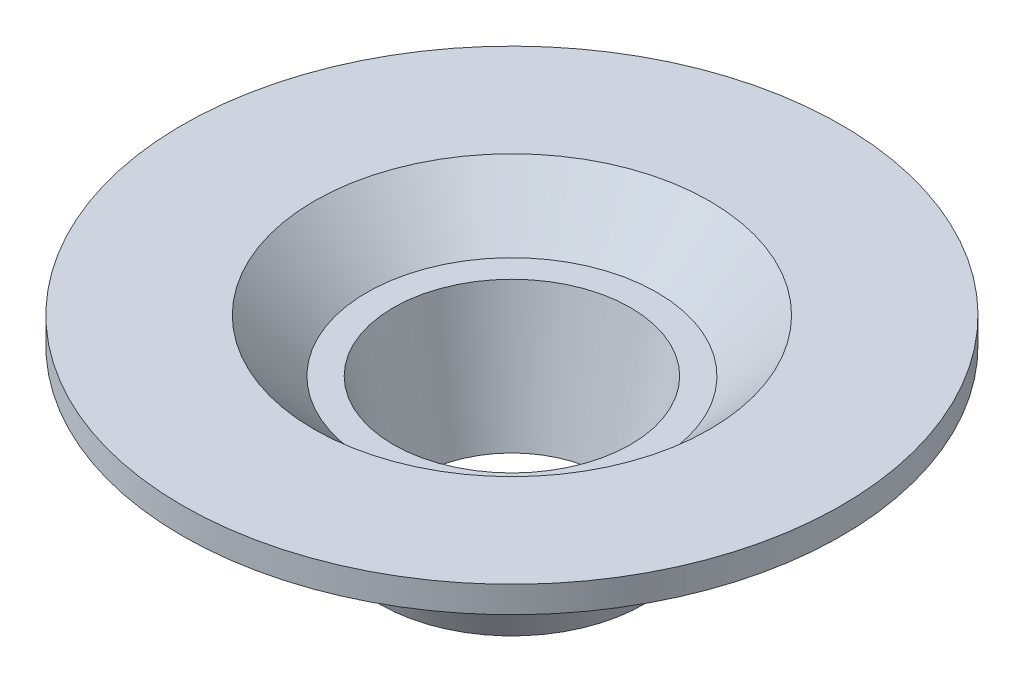
SolidWorks part; units mm, degrees
ref_plane "Front Plane" through (0, 0, 0) normal (0, 0, 1) x (1, 0, 0)
ref_plane "Top Plane" through (0, 0, 0) normal (0, 1, 0) x (1, 0, 0)
ref_plane "Right Plane" through (0, 0, 0) normal (1, 0, 0) x (0, 0, -1)
sketch "Sketch1" plane through (0, 0, 0) normal (1, 0, 0) x (0, 0, -1)
  line L0 (0, 0) -> (0, -5) construction
  line L1 (3.5, -5) -> (4.5, 0)
  line L2 (4.5, 0) -> (5.5, 0)
  line L3 (5.5, 0) -> (7.5, 2)
  line L4 (7.5, 2) -> (12.5, 2)
  line L5 (12.5, 2) -> (12.5, 1)
  line L6 (12.5, 1) -> (10.5, 1)
  line L7 (10.5, 1) -> (8.5, -1)
  line L8 (8.5, -1) -> (6.5, -1)
  line L9 (6.5, -1) -> (5, -5)
  line L10 (5, -5) -> (3.5, -5)
  point P5 (0, 0)
  point P14 (4.5156, 0)
  point P15 (5.0204, 0)
  point P16 (5.2331, 0)
  point P17 (0, 0)
  point P18 (5.8763, -0.7653)
  point P19 (0, 0)
  point P21 (5.822, 1.3268)
  dimension "D1" = 5
  dimension "D2" = 12.5
  dimension "D3" = 1.5
  dimension "D4" = 3.5
  dimension "D5" = 4.5
  dimension "D6" = 6.5
  dimension "D7" = 4
  dimension "D8" = 2
  dimension "D9" = 2
  dimension "D10" = 1
  dimension "D11" = 2
  dimension "D12" = 1
revolve "Revolve1" add sketch "Sketch1" angle 360 about L0
